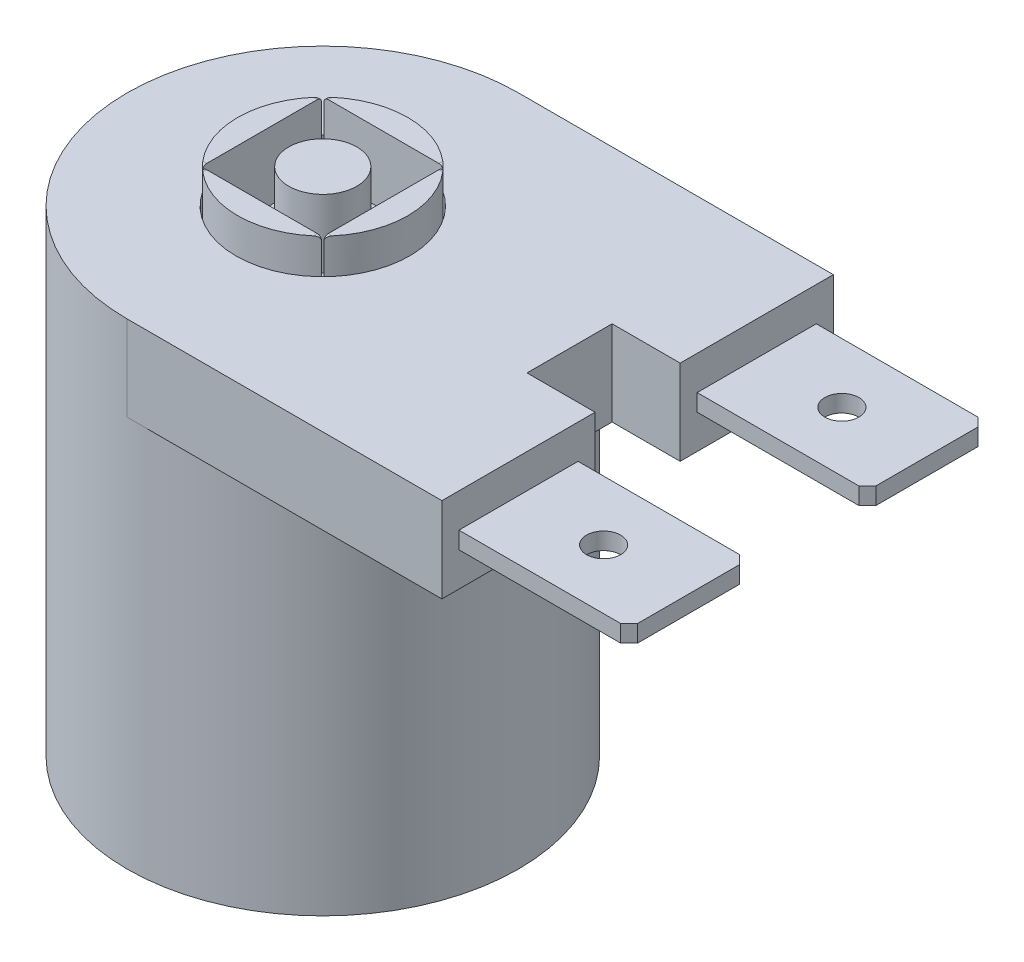
SolidWorks part; units mm, degrees
ref_plane "Спереди" through (0, 0, 0) normal (0, 0, 1) x (1, 0, 0)
ref_plane "Сверху" through (0, 0, 0) normal (0, 1, 0) x (1, 0, 0)
ref_plane "Справа" through (0, 0, 0) normal (1, 0, 0) x (0, 0, -1)
sketch "Эскиз1" plane through (0, 0, 0) normal (0, 1, 0) x (1, 0, 0)
  circle A0 centre (0, 0) radius 11.5
extrude "Бобышка-Вытянуть1" add sketch "Эскиз1" along normal blind 28
sketch "Эскиз2" plane through (0, 28, 0) normal (0, 1, 0) x (1, 0, 0)
  line L0 (-11.5, 0) -> (18.5, 0) construction
  line L1 (0, 11.5) -> (18.5, 11.5)
  line L2 (18.5, 11.5) -> (18.5, 2.5)
  line L3 (18.5, 2.5) -> (14.5, 2.5)
  line L4 (14.5, 2.5) -> (14.5, -2.5)
  line L5 (18.5, -2.5) -> (14.5, -2.5)
  line L6 (18.5, -11.5) -> (18.5, -2.5)
  line L7 (0, -11.5) -> (18.5, -11.5)
  circle A0 centre (0, 0) radius 11.5 construction
  arc A1 (0, -11.5) -> (0, 11.5) centre (0, 0) ccw
  point P13 (14.5, 0)
extrude "Бобышка-Вытянуть2" add sketch "Эскиз2" against normal blind 5
sketch "Эскиз3" plane through (18.5, 0, 0) normal (1, 0, 0) x (0, 0, -1)
  line L0 (-10.5, 26) -> (-3.5, 26)
  line L1 (-3.5, 26) -> (-3.5, 25)
  line L2 (-10.5, 26) -> (-10.5, 25)
  line L3 (-10.5, 25) -> (-3.5, 25)
  line L4 (0, 28) -> (0, 23) construction
  line L7 (-2.5, 28) -> (2.5, 28) construction
  line L8 (-2.5, 23) -> (2.5, 23) construction
  line L9 (10.5, 25) -> (3.5, 25)
  line L10 (10.5, 26) -> (10.5, 25)
  line L11 (3.5, 26) -> (3.5, 25)
  line L12 (10.5, 26) -> (3.5, 26)
  dimension "D1" = 1
  dimension "D2" = 7
extrude "Бобышка-Вытянуть3" add sketch "Эскиз3" along normal blind 10
chamfer "Фаска1" distance 0.5 angle 45 4 edges at (28.5, 25.5, 10.5) (28.5, 25.5, 3.5) (28.5, 25.5, -3.5) (28.5, 25.5, -10.5)
sketch "Эскиз4" plane through (0, 26, 0) normal (0, 1, 0) x (1, 0, 0)
  line L0 (18.5, -3.5) -> (18.5, -10.5) construction
  line L2 (18.5, 2.5) -> (18.5, 11.5) construction
  circle A0 centre (23.5, -7) radius 1
  circle A1 centre (23.5, 7) radius 1
  dimension "D1" = 2
  dimension "D2" = 2
  dimension "D3" = 5
  dimension "D4" = 5
extrude "Вырез-Вытянуть1" cut sketch "Эскиз4" against normal blind 9
sketch "Эскиз5" plane through (0, 28, 0) normal (0, 1, 0) x (1, 0, 0)
  circle A0 centre (0, 0) radius 5.1
extrude "Вырез-Вытянуть3" cut sketch "Эскиз5" against normal blind 2
sketch "Эскиз7" plane through (0, 26, 0) normal (0, 1, 0) x (1, 0, 0)
  line L0 (-3.5707, 3.5) -> (-3.5707, -3.5)
  line L1 (3.5, 3.5707) -> (-3.5, 3.5707)
  line L2 (3.5707, -3.5) -> (3.5707, 3.5)
  line L3 (-3.5, -3.5707) -> (3.5, -3.5707)
  circle A0 centre (0, 0) radius 2
  arc A1 (3.5, 3.5707) -> (-3.5, 3.5707) centre (0, 0) ccw
  arc A2 (3.5707, -3.5) -> (3.5707, 3.5) centre (0, 0) ccw
  arc A3 (-3.5707, 3.5) -> (-3.5707, -3.5) centre (0, 0) ccw
  arc A4 (-3.5, -3.5707) -> (3.5, -3.5707) centre (0, 0) ccw
  point P10 (0, 0)
  dimension "D1" = 7
extrude "Бобышка-Вытянуть5" add sketch "Эскиз7" along normal blind 4
sketch "Эскиз8" plane through (3.5707, 0, 0) normal (-1, 0, 0) x (0, 0, 1)
  line L0 (-3.5, 30) -> (-3.5, 29.75)
  line L5 (-3.25, 30) -> (-3.5, 30)
  line L6 (0, 30) -> (0, 29.369) construction
  line L7 (3.5, 30) -> (-3.5, 30) construction
  line L8 (3.25, 30) -> (3.5, 30)
  line L9 (3.5, 30) -> (3.5, 29.75)
  arc A0 (-3.25, 30) -> (-3.5, 29.75) centre (-3.25, 29.75) ccw
  arc A1 (3.25, 30) -> (3.5, 29.75) centre (3.25, 29.75) cw
extrude "Вырез-Вытянуть4" cut sketch "Эскиз8" against normal blind 4 and the other way blind 24
sketch "Эскиз9" plane through (0, 0, -3.5707) normal (0, 0, 1) x (1, 0, 0)
  line L0 (-3.5, 30) -> (-3.5, 29.75)
  line L1 (-3.25, 30) -> (-3.5, 30)
  line L2 (0, 30) -> (0, 29.369) construction
  line L3 (3.25, 30) -> (3.5, 30)
  line L4 (3.5, 30) -> (3.5, 29.75)
  arc A0 (-3.25, 30) -> (-3.5, 29.75) centre (-3.25, 29.75) ccw
  arc A1 (3.25, 30) -> (3.5, 29.75) centre (3.25, 29.75) cw
extrude "Вырез-Вытянуть5" cut sketch "Эскиз9" against normal blind 4 and the other way blind 24
